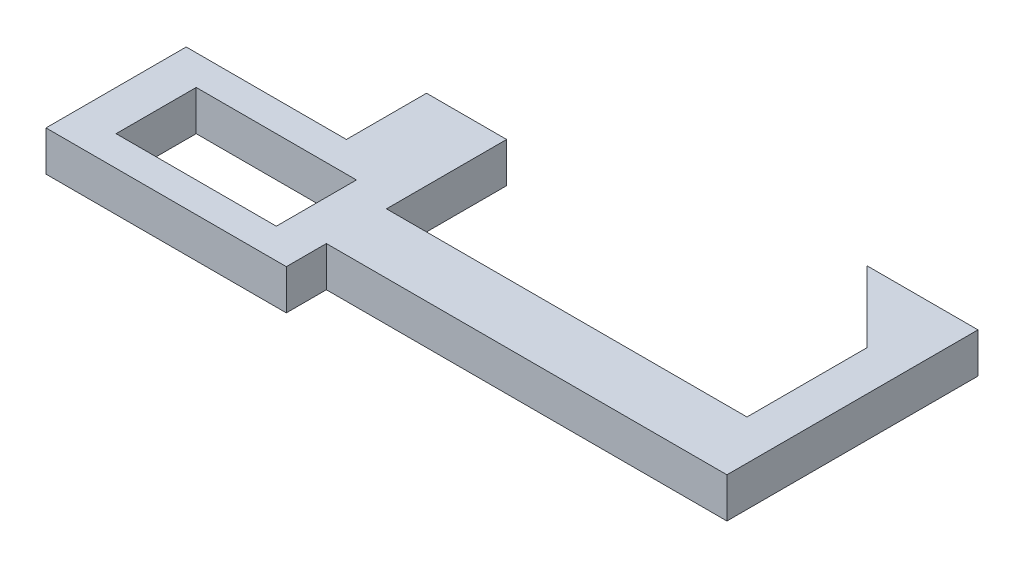
SolidWorks part; units mm, degrees
ref_plane "Front Plane" through (0, 0, 0) normal (0, 0, 1) x (1, 0, 0)
ref_plane "Top Plane" through (0, 0, 0) normal (0, 1, 0) x (1, 0, 0)
ref_plane "Right Plane" through (0, 0, 0) normal (1, 0, 0) x (0, 0, -1)
sketch "Sketch1" plane through (0, 0, 0) normal (0, 1, 0) x (1, 0, 0)
  line L0 (-27.9733, 22.1922) -> (-23.4733, 22.1922)
  line L1 (-23.4733, 22.1922) -> (-23.4733, 23.6922)
  line L2 (-23.4733, 23.6922) -> (-24.3572, 24.5761)
  line L3 (-24.3572, 24.5761) -> (-22.9733, 24.5761)
  line L4 (-22.9733, 24.5761) -> (-22.9733, 21.4422)
  line L5 (-27.9733, 22.1922) -> (-27.9733, 21.4422)
  line L6 (-27.9733, 21.4422) -> (-22.9733, 21.4422)
  line L7 (-27.9733, 22.1922) -> (-27.9733, 22.6922)
  line L8 (-27.9733, 22.6922) -> (-30.9733, 22.6922)
  line L9 (-27.9733, 21.4422) -> (-27.9733, 20.9422)
  line L10 (-27.9733, 20.9422) -> (-30.9733, 20.9422)
  line L11 (-30.9733, 20.9422) -> (-30.9733, 22.6922)
  line L12 (-27.9733, 22.6922) -> (-27.9733, 23.6922)
  line L13 (-27.9733, 23.6922) -> (-28.9733, 23.6922)
  line L14 (-28.9733, 23.6922) -> (-28.9733, 22.6922)
  line L15 (-30.9733, 21.8172) -> (-29.4733, 21.8172)
  line L16 (-29.4733, 21.8172) -> (-29.4733, 22.3172)
  line L17 (-29.4733, 22.3172) -> (-28.4733, 22.3172)
  line L18 (-28.4733, 22.3172) -> (-28.4733, 21.3172)
  line L19 (-28.4733, 21.3172) -> (-30.4733, 21.3172)
  line L20 (-30.4733, 21.3172) -> (-30.4733, 22.3172)
  line L21 (-30.4733, 22.3172) -> (-29.4733, 22.3172)
extrude "Boss-Extrude1" add sketch "Sketch1" along normal blind 0.5 contours L11 L10 L9 L5 L7 L8 | L5 L6 L4 L3 L2 L1 L0 | L13 L14 L8 L12
